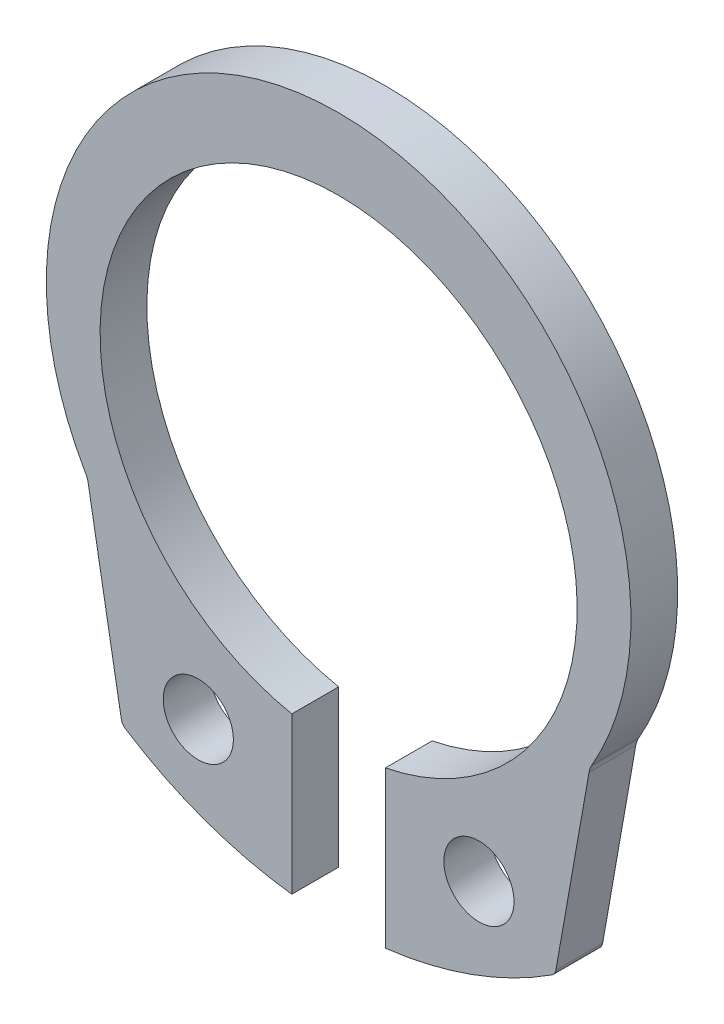
SolidWorks part; units mm, degrees
ref_plane "Front" through (0, 0, 0) normal (0, 0, 1) x (1, 0, 0)
ref_plane "Top" through (0, 0, 0) normal (0, 1, 0) x (1, 0, 0)
ref_plane "Right" through (0, 0, 0) normal (1, 0, 0) x (0, 0, -1)
sketch "Sketch1" plane through (0, 0, 0) normal (0, 0, 1) x (1, 0, 0)
  line L0 (0, 4.2365) -> (0, -4.9012) construction
  line L1 (-1, -5.381) -> (-1, -8.7203)
  line L2 (1, -5.381) -> (1, -8.7203)
  line L3 (6.8, -0.38) -> (-6.8, -0.38) construction
  line L4 (5.3694, -3.1988) -> (4.6306, -7.3884)
  line L7 (-5.3694, -3.1988) -> (-4.6306, -7.3884)
  line L8 (-5.3694, -3.1988) -> (-5.3694, -11.2695) construction
  arc A0 (1, -5.381) -> (-1, -5.381) centre (0, -0.38) ccw
  arc A1 (5.3694, -3.1988) -> (-5.3694, -3.1988) centre (0, 0) ccw
  arc A2 (-6.8, -0.38) -> (6.8, -0.38) centre (0, -0.38) ccw construction
  arc A3 (4.6306, -7.3884) -> (1, -8.7203) centre (0, -0.38) cw
  arc A4 (-4.6306, -7.3884) -> (-1, -8.7203) centre (0, -0.38) ccw
  circle A5 centre (3, -6.4825) radius 0.75
  circle A6 centre (-3, -6.4825) radius 0.75
  point P17 (-5, -5.2936)
  dimension "d" = 10.2
  dimension "D2" = 10
  dimension "d0" = 12.5
  dimension "d1" = 1.5
  dimension "R1" = 6.8
  dimension "R" = 8.4
  dimension "B1" = 2
  dimension "C" = 0.38
  dimension "L" = 10
  dimension "B2" = 6
extrude "Body" add sketch "Sketch1" against normal blind 1
fillet "Fillet1" radius 0.2 2 edges at (-4.6306, -7.3884, -0.5) (4.6306, -7.3884, -0.5)
fillet "Fillet2" radius 0.5 2 edges at (5.3694, -3.1988, -0.5) (-5.3694, -3.1988, -0.5)
